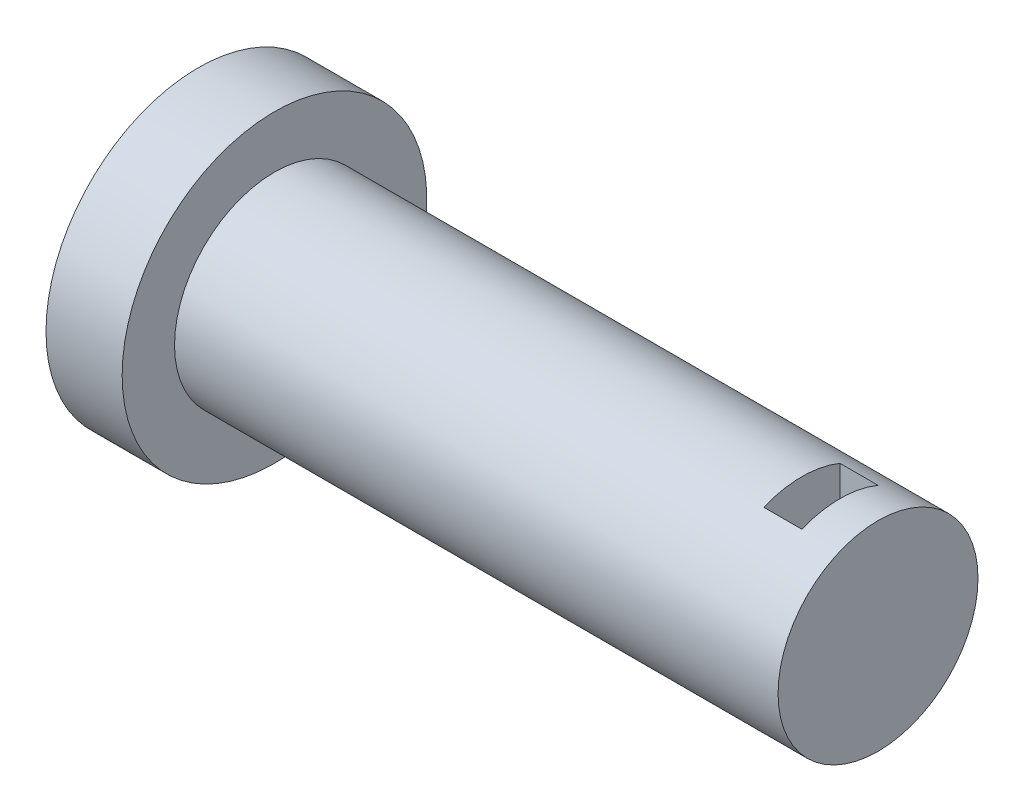
SolidWorks part; units mm, degrees
material "Brass"
ref_plane "Front Plane" through (0, 0, 0) normal (0, 0, 1) x (1, 0, 0)
ref_plane "Top Plane" through (0, 0, 0) normal (0, 1, 0) x (1, 0, 0)
ref_plane "Right Plane" through (0, 0, 0) normal (1, 0, 0) x (0, 0, -1)
sketch "Sketch1" plane through (0, 0, 0) normal (1, 0, 0) x (0, 0, -1)
  circle A0 centre (0, 0) radius 26.25
extrude "Boss-Extrude1" add sketch "Sketch1" along normal blind 158.5
sketch "Sketch2" plane through (0, 0, 0) normal (-1, 0, 0) x (0, 0, 1)
  circle A0 centre (0, 0) radius 40
extrude "Boss-Extrude2" add sketch "Sketch2" along normal blind 20
sketch "Sketch3" plane through (0, 0, 0) normal (0, 1, 0) x (1, 0, 0)
  line L0 (158.5, -26.25) -> (158.5, 26.25) construction
  line L1 (138.5, 10) -> (148.5, 10)
  line L2 (138.5, 10) -> (138.5, -10)
  line L3 (138.5, -10) -> (148.5, -10)
  line L4 (148.5, 10) -> (148.5, -10)
  line L5 (158.5, 26.25) -> (0, 26.25) construction
  dimension "D1" = 10
  dimension "D2" = 10
  dimension "D3" = 20
  dimension "D4" = 16.25
extrude "Cut-Extrude1" cut sketch "Sketch3" against normal through all both and the other way through all
